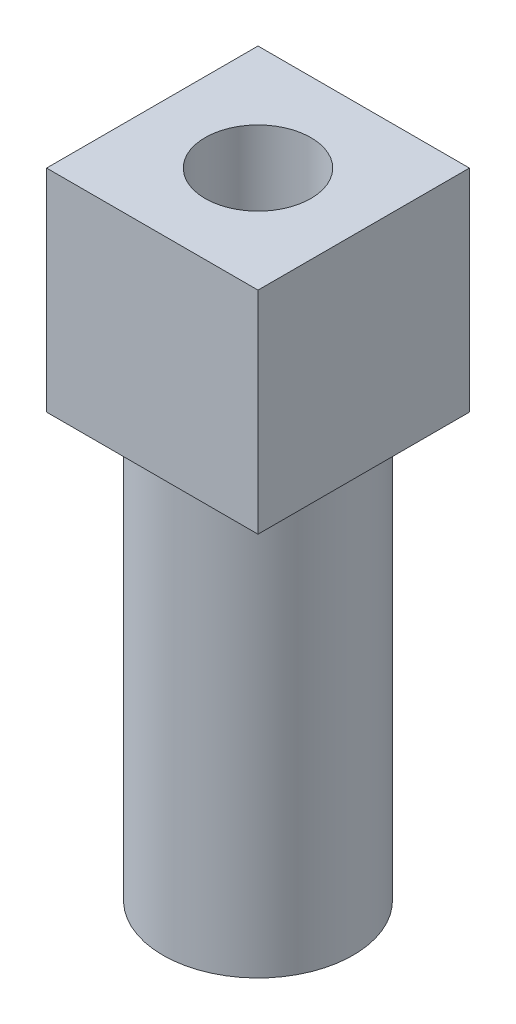
SolidWorks part; units mm, degrees
ref_plane "Ebene vorne" through (0, 0, 0) normal (0, 0, 1) x (1, 0, 0)
ref_plane "Ebene oben" through (0, 0, 0) normal (0, 1, 0) x (1, 0, 0)
ref_plane "Ebene rechts" through (0, 0, 0) normal (1, 0, 0) x (0, 0, -1)
sketch "Skizze1" plane through (0, 0, 0) normal (0, 0, 1) x (1, 0, 0)
  line L0 (0, 0) -> (4.5, 0)
  line L1 (4.5, 0) -> (4.5, 20)
  line L2 (0, 20) -> (4.5, 20)
  line L4 (0, -2.4593) -> (0, 22.5998) construction
  line L6 (0, 20) -> (0, 0)
  dimension "D1" = 4.5
  dimension "D2" = 20
revolve "Rotation1" add sketch "Skizze1" angle 360 about L4
sketch "Skizze5" plane through (0, 20, 0) normal (0, 1, 0) x (1, 0, 0)
  line L0 (0, 5) -> (0, -5) construction
  line L1 (-5, 5) -> (5, 5)
  line L2 (-5, 5) -> (-5, -5)
  line L3 (-5, -5) -> (5, -5)
  line L4 (5, 5) -> (5, -5)
  line L5 (5, 0) -> (-5, 0) construction
  dimension "D1" = 10
extrude "Aufsatz-Linear austragen1" add sketch "Skizze5" along normal blind 10
sketch "Sketch1" plane through (0, 30, 0) normal (0, 1, 0) x (1, 0, 0)
  circle A0 centre (0, 0) radius 2.5
extrude "Cut-Extrude1" cut sketch "Sketch1" against normal through all
